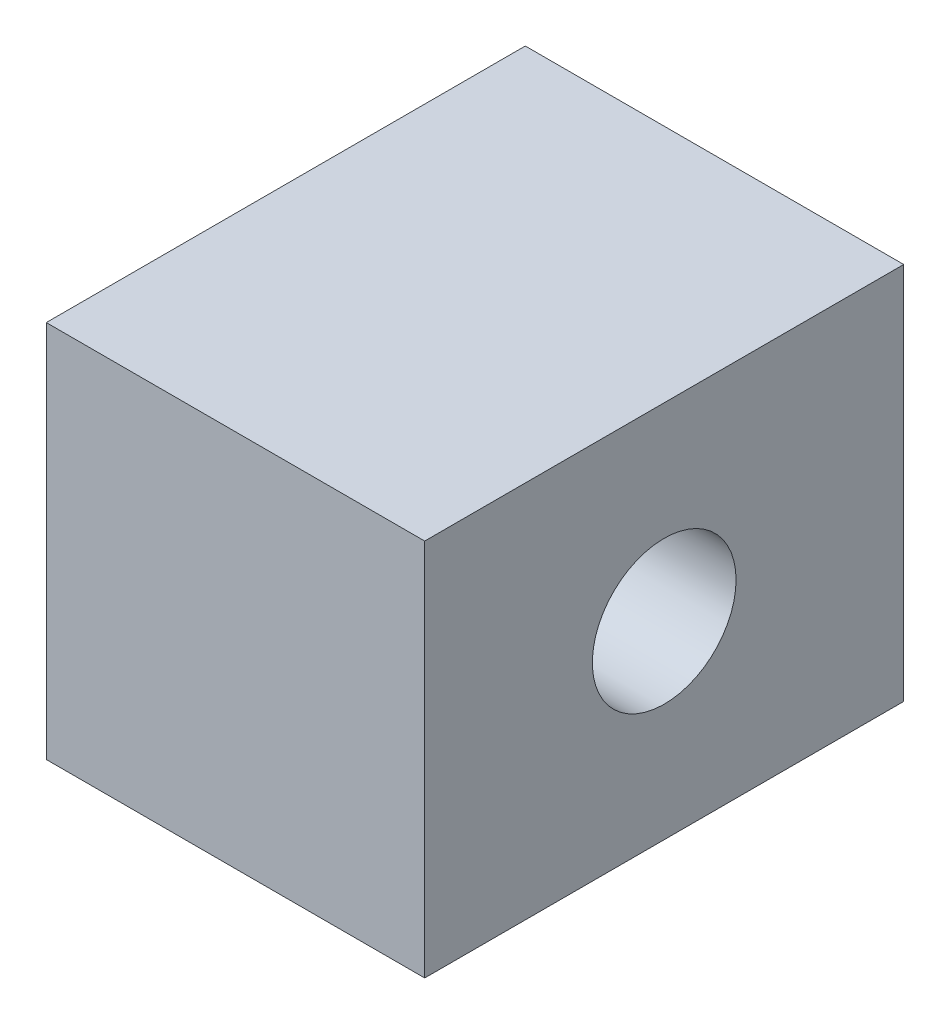
SolidWorks part; units mm, degrees
ref_plane "Płaszczyzna przednia" through (0, 0, 0) normal (0, 0, 1) x (1, 0, 0)
ref_plane "Płaszczyzna górna" through (0, 0, 0) normal (0, 1, 0) x (1, 0, 0)
ref_plane "Płaszczyzna prawa" through (0, 0, 0) normal (1, 0, 0) x (0, 0, -1)
sketch "Szkic1" plane through (0, 0, 0) normal (0, 0, 1) x (1, 0, 0)
  line L1 (0, 0) -> (15.8, 0)
  line L2 (0, 0) -> (0, 15.8)
  line L3 (0, 15.8) -> (15.8, 15.8)
  line L4 (15.8, 0) -> (15.8, 15.8)
  dimension "D1" = 15.8
extrude "Dodanie-wyciągnięcie1" add sketch "Szkic1" along normal blind 20
sketch "Szkic2" plane through (15.8, 0, 0) normal (1, 0, 0) x (0, 0, -1)
  line L0 (0, 0) -> (0, 15.8) construction
  line L1 (-20, 15.8) -> (0, 15.8) construction
  circle A0 centre (-10, 7.9) radius 3
  dimension "D2" = 7.9
  dimension "D3" = 6
  dimension "D1" = 10
extrude "Wytnij-wyciągnięcie1" cut sketch "Szkic2" against normal blind 20
